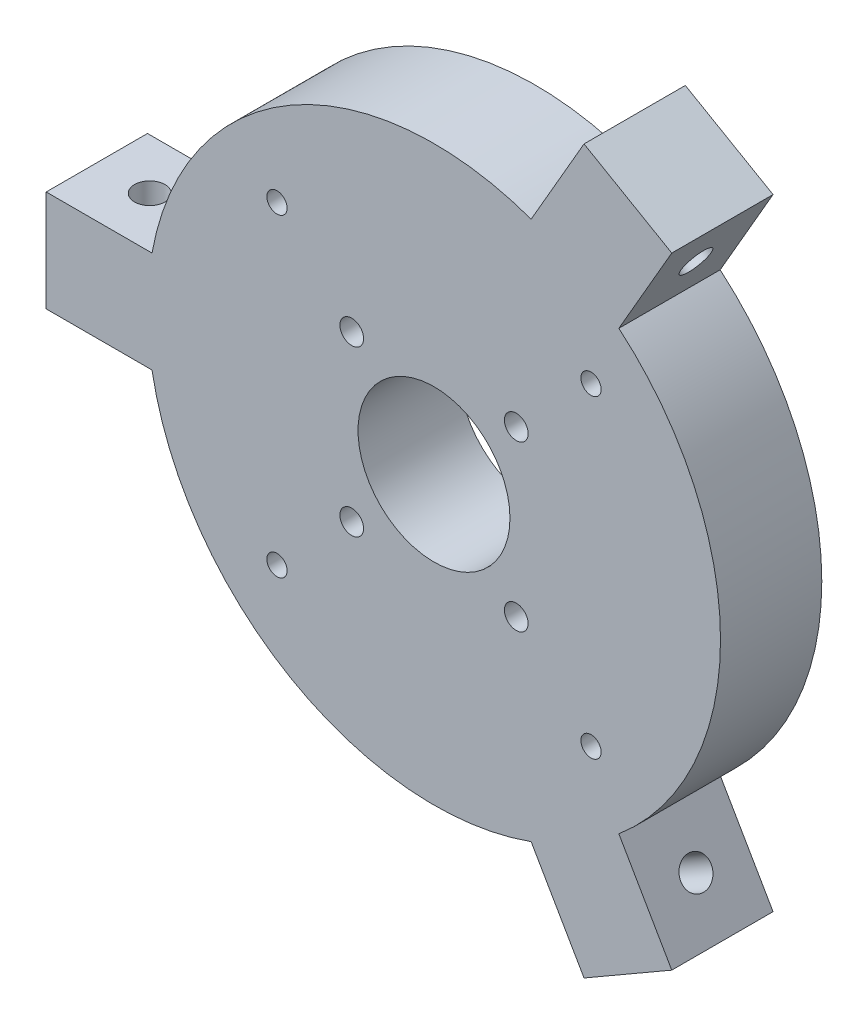
SolidWorks part; units mm, degrees
ref_plane "前视基准面" through (0, 0, 0) normal (0, 0, 1) x (1, 0, 0)
ref_plane "上视基准面" through (0, 0, 0) normal (0, 1, 0) x (1, 0, 0)
ref_plane "右视基准面" through (0, 0, 0) normal (1, 0, 0) x (0, 0, -1)
other "Configuration Table"
sketch "草图1" plane through (0, 0, 0) normal (0, 0, 1) x (1, 0, 0)
  line L1 (-40, 40) -> (40, 40)
  line L2 (-40, 40) -> (-40, -40)
  line L3 (-40, -40) -> (40, -40)
  line L4 (40, 40) -> (40, -40)
  line L5 (-40, 40) -> (40, -40) construction
  line L6 (-40, -40) -> (40, 40) construction
  point P0 (0, 0)
  dimension "D1" = 80
  dimension "D2" = 80
extrude "凸台-拉伸1" add sketch "草图1" along normal blind 20
sketch "草图2" plane through (0, 0, 20) normal (0, 0, 1) x (1, 0, 0)
  circle A0 centre (0, 0) radius 15
extrude "切除-拉伸1" cut sketch "草图2" against normal blind 20
sketch "草图3" plane through (0, 0, 20) normal (0, 0, 1) x (1, 0, 0)
  circle A0 centre (31, 31) radius 2
extrude "切除-拉伸2" cut sketch "草图3" against normal blind 20
pattern_circular "阵列(圆周)1" count 4 over 360 about axis through (0, 0, 0) along (0, 0, 1) of "切除-拉伸2"
sketch "草图4" plane through (0, 0, 20) normal (0, 0, 1) x (1, 0, 0)
  circle A0 centre (16.24, 16.24) radius 2.34
extrude "切除-拉伸3" cut sketch "草图4" against normal blind 20
pattern_circular "阵列(圆周)2" count 4 over 360 about axis through (0, 0, 0) along (0, 0, 1) of "切除-拉伸3"
sketch "草图5" plane through (0, 0, 0) normal (0, 0, -1) x (-1, 0, 0)
  line L0 (40, -40) -> (-40, -40)
  line L4 (40, 40) -> (40, -40)
  line L5 (-40, -40) -> (-40, 40)
  line L6 (-40, 40) -> (40, 40)
  circle A0 centre (0, 0) radius 56.5685
  line M15 (-40, 40) -> (-40, -40)
  line M16 (-40, -40) -> (40, -40)
  line M17 (40, -40) -> (40, 40)
  line M18 (40, 40) -> (-40, 40)
extrude "凸台-拉伸3" add sketch "草图5" against normal blind 20 contours A0 M17 | A0 M16 | A0 M15 | A0 M18
sketch "草图6" plane through (0, 0, 0) normal (0, 0, -1) x (-1, 0, 0)
  line L0 (55.6776, 10) -> (55.6776, -10)
  line L1 (76.5685, 0) -> (76.5685, 10)
  line L2 (76.5685, 0) -> (76.5685, -10)
  line L3 (76.5685, 10) -> (55.6776, 10)
  line L4 (76.5685, -10) -> (55.6776, -10)
  circle A0 centre (0, 0) radius 56.5685 construction
  circle A2 centre (0, 0) radius 56.5685
  arc A3 (55.6776, 10) -> (55.6776, -10) centre (0, 0) ccw
  circle M1 centre (-16.24, -16.24) radius 2.34
  circle M2 centre (16.24, -16.24) radius 2.34
  circle M3 centre (16.24, 16.24) radius 2.34
  circle M4 centre (-16.24, 16.24) radius 2.34
  circle M5 centre (31, 31) radius 2
  circle M6 centre (31, -31) radius 2
  circle M7 centre (-31, -31) radius 2
  circle M8 centre (-31, 31) radius 2
  circle M9 centre (0, 0) radius 15
  circle M10 centre (0, 0) radius 56.5685
  dimension "D1" = 0
extrude "凸台-拉伸4" add sketch "草图6" against normal blind 20 contours L0 M10 M2 M4 M6 M8 M9 M7 M5 M3 M1 | L4 L2 L1 L3 M10 | M9
sketch "草图7" plane through (0, -10, 0) normal (0, -1, 0) x (-1, 0, 0)
  circle A0 centre (66.1231, -10) radius 3
extrude "切除-拉伸4" cut sketch "草图7" against normal through all
pattern_circular "阵列(圆周)3" count 3 over 360 about axis through (0, 0, 0) along (0, 0, 1) of "切除-拉伸4", "凸台-拉伸4"
